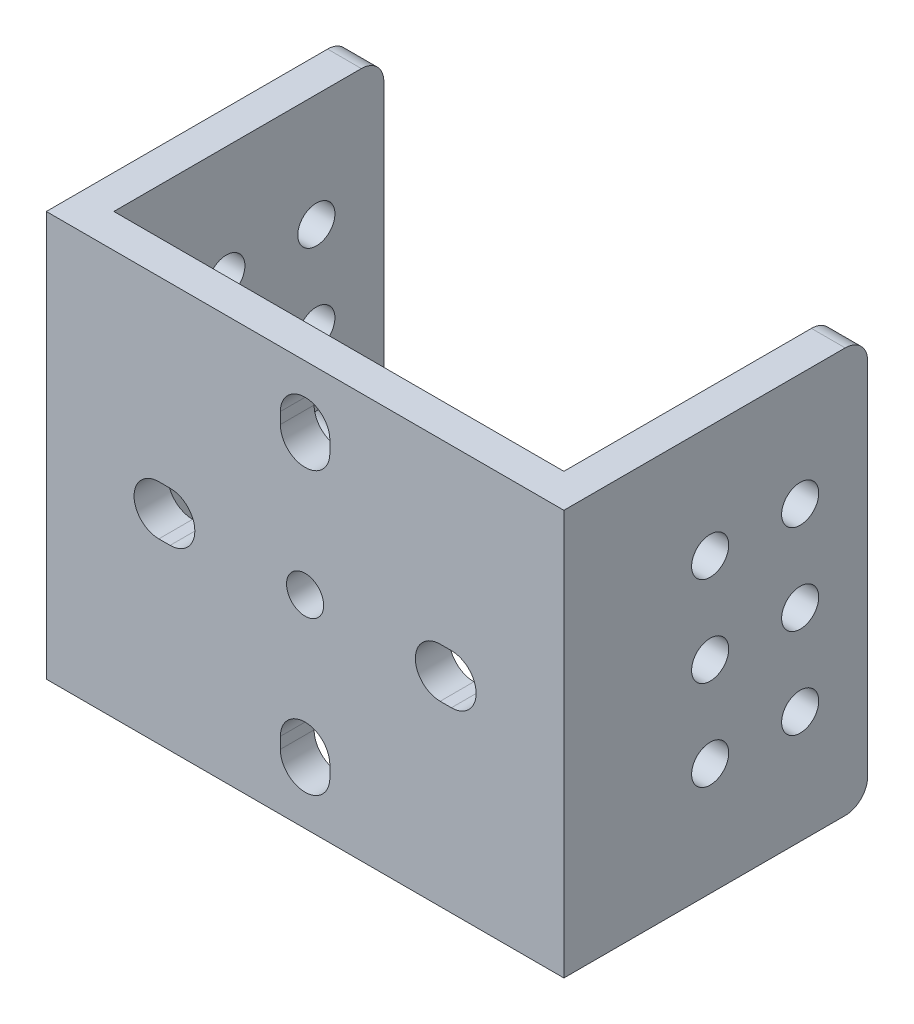
SolidWorks part; units mm, degrees
ref_plane "前视基准面" through (0, 0, 0) normal (0, 0, 1) x (1, 0, 0)
ref_plane "上视基准面" through (0, 0, 0) normal (0, 1, 0) x (1, 0, 0)
ref_plane "右视基准面" through (0, 0, 0) normal (1, 0, 0) x (0, 0, -1)
sketch "草图1" plane through (0, 0, 0) normal (0, 0, 1) x (1, 0, 0)
  line L0 (0, 36) -> (46, 0)
  line L1 (0, 0) -> (46, 0)
  line L2 (0, 0) -> (0, 36)
  line L3 (0, 36) -> (46, 36)
  line L4 (46, 0) -> (46, 36)
  line L5 (20.8, 31) -> (20.8, 30)
  line L6 (25.2, 31) -> (25.2, 30)
  line L7 (35, 20.2) -> (36, 20.2)
  line L8 (36, 15.8) -> (35, 15.8)
  line L9 (25.2, 6) -> (25.2, 5)
  line L10 (20.8, 6) -> (20.8, 5)
  line L11 (10, 20.2) -> (11, 20.2)
  line L12 (10, 15.8) -> (11, 15.8)
  circle A0 centre (23, 18) radius 1.65
  circle A1 centre (23, 18) radius 12
  circle A2 centre (23, 18) radius 13
  circle A3 centre (23, 31) radius 2.2
  circle A4 centre (23, 30) radius 2.2
  circle A5 centre (35, 18) radius 2.2
  circle A6 centre (36, 18) radius 2.2
  circle A7 centre (23, 6) radius 2.2
  circle A8 centre (23, 5) radius 2.2
  circle A9 centre (10, 18) radius 2.2
  circle A10 centre (11, 18) radius 2.2
extrude "凸台-拉伸1" add sketch "草图1" along normal blind 3
sketch "草图2" plane through (0, 0, 0) normal (0, 0, 1) x (1, 0, 0)
  line L1 (0, 36) -> (0, 0)
  line L2 (0, 36) -> (3, 36)
  line L3 (0, 0) -> (3, 0)
  line L4 (3, 36) -> (3, 0)
  line L6 (46, 0) -> (46, 36)
  line L7 (46, 0) -> (43, 0)
  line L8 (46, 36) -> (43, 36)
  line L9 (43, 0) -> (43, 36)
extrude "凸台-拉伸2" add sketch "草图2" against normal blind 24
sketch "草图3" plane through (46, 0, 0) normal (1, 0, 0) x (0, 0, -1)
  line L2 (-3, 36) -> (8, 36)
  line L3 (-3, 0) -> (8, 0)
  line L5 (-3, 36) -> (24, 36) construction
  line L6 (-3, 0) -> (24, 0) construction
  line L7 (8, 0) -> (8, 36)
  line L8 (8, 36) -> (24, 0)
  line L9 (16, 18) -> (8, 18)
  circle A0 centre (10, 10) radius 1.65
  circle A1 centre (10, 18) radius 1.65
  circle A3 centre (18, 26) radius 1.65
  circle A4 centre (18, 10) radius 1.65
  circle A6 centre (18, 18) radius 1.65
  circle A8 centre (10, 26) radius 1.65
extrude "切除-拉伸1" cut sketch "草图3" against normal blind 50
fillet "圆角1" radius 2 4 edges at (1.5, 36, -24) (1.5, 0, -24) (44.5, 0, -24) (44.5, 36, -24)
